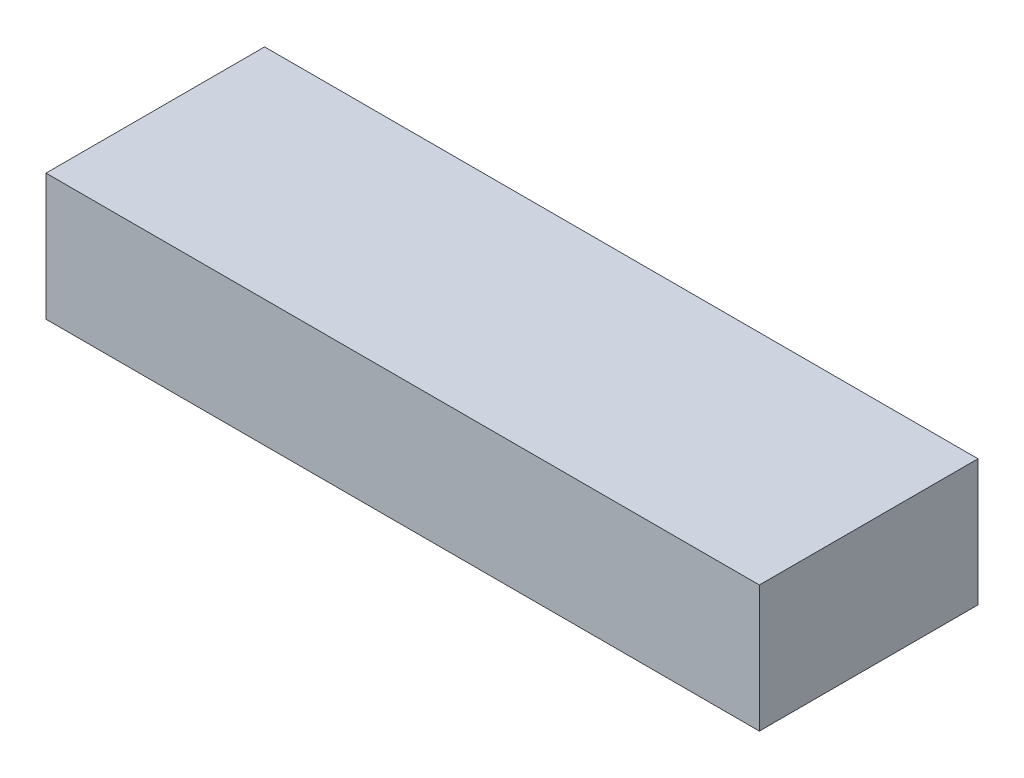
SolidWorks part; units mm, degrees
ref_plane "Front Plane" through (0, 0, 0) normal (0, 0, 1) x (1, 0, 0)
ref_plane "Top Plane" through (0, 0, 0) normal (0, 1, 0) x (1, 0, 0)
ref_plane "Right Plane" through (0, 0, 0) normal (1, 0, 0) x (0, 0, -1)
sketch "Sketch1" plane through (0, 0, 0) normal (0, 0, 1) x (1, 0, 0)
  line L1 (0, 0) -> (62, 0)
  line L2 (0, 0) -> (0, 11)
  line L3 (0, 11) -> (62, 11)
  line L4 (62, 0) -> (62, 11)
  dimension "D1" = 62
  dimension "D2" = 11
extrude "Boss-Extrude1" add sketch "Sketch1" along normal blind 19
